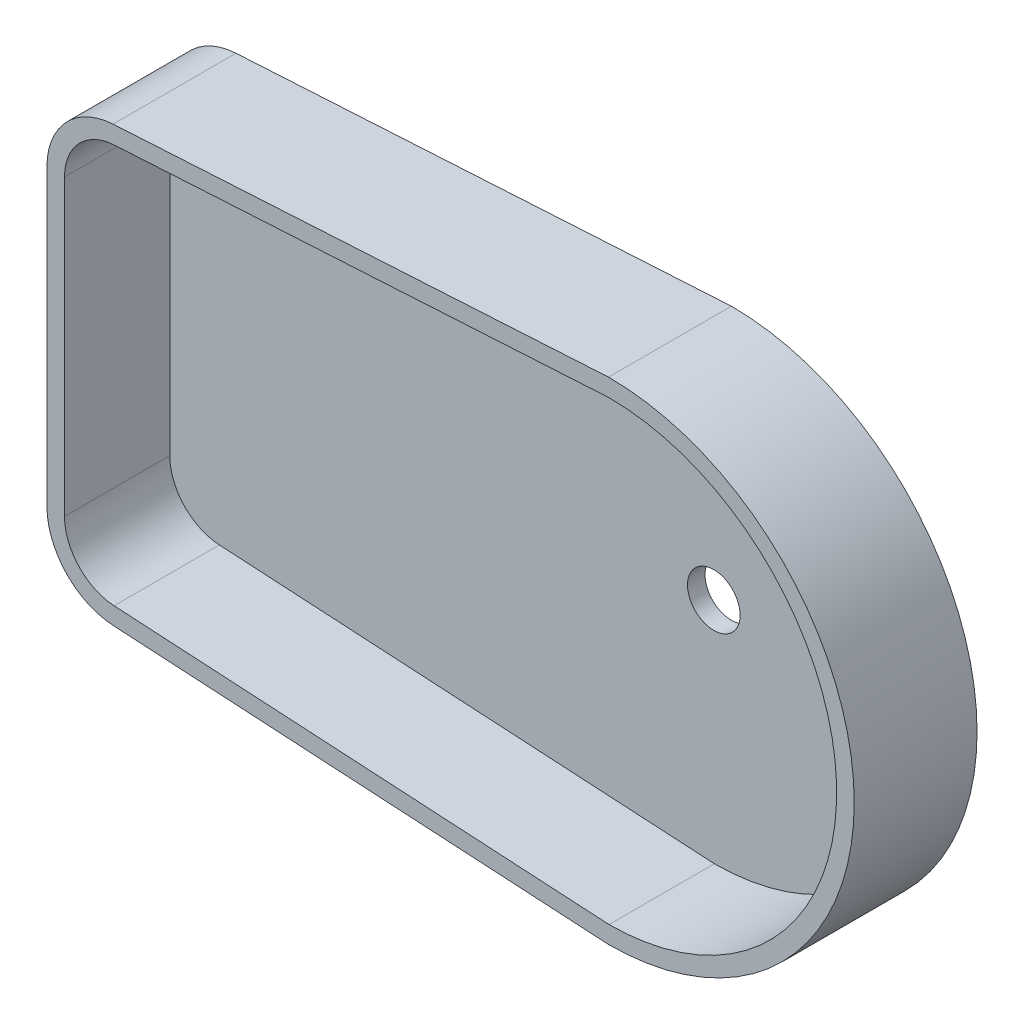
SolidWorks part; units mm, degrees
ref_plane "Front Plane" through (0, 0, 0) normal (0, 0, 1) x (1, 0, 0)
ref_plane "Top Plane" through (0, 0, 0) normal (0, 1, 0) x (1, 0, 0)
ref_plane "Right Plane" through (0, 0, 0) normal (1, 0, 0) x (0, 0, -1)
sketch "Sketch4" plane through (0, 0, 0) normal (0, 0, 1) x (1, 0, 0)
  line L0 (0, 0) -> (230, 0) construction
  line L1 (160, 107.8742) -> (160, -118.0659) construction
  line L2 (0, 41.8729) -> (0, -41.8729)
  line L3 (18.8457, 61.8395) -> (160, 70)
  line L4 (18.8457, -61.8395) -> (160, -70)
  arc A0 (160, -70) -> (160, 70) centre (160, 0) ccw
  arc A1 (18.8457, -61.8395) -> (0, -41.8729) centre (20, -41.8729) cw
  arc A2 (18.8457, 61.8395) -> (0, 41.8729) centre (20, 41.8729) ccw
  point P12 (0, -60.75)
  point P15 (0, 60.75)
  dimension "D3" = 140
  dimension "D5" = 20
  dimension "D1" = 230
  dimension "D2" = 70
  dimension "D4" = 121.5
extrude "Boss-Extrude1" add sketch "Sketch4" along normal mid plane 35
sketch "Sketch5" plane through (0, 0, 17.5) normal (0, 0, 1) x (1, 0, 0)
  line L7 (160.1417, 64.9998) -> (19.1343, 56.8479)
  line L8 (5, 41.8729) -> (5, -41.8729)
  line L9 (19.1343, -56.8479) -> (160.1417, -64.9998)
  line L10 (160.1417, 64.9998) -> (19.1343, 56.8479)
  line L11 (5, 41.8729) -> (5, -41.8729)
  line L12 (19.1343, -56.8479) -> (160.1417, -64.9998)
  arc A6 (160.1417, -64.9998) -> (160.1417, 64.9998) centre (160, 0) ccw
  arc A7 (19.1343, 56.8479) -> (5, 41.8729) centre (20, 41.8729) ccw
  arc A8 (5, -41.8729) -> (19.1343, -56.8479) centre (20, -41.8729) ccw
  arc A9 (160.1417, -64.9998) -> (160.1417, 64.9998) centre (160, 0) ccw
  arc A10 (19.1343, 56.8479) -> (5, 41.8729) centre (20, 41.8729) ccw
  arc A11 (5, -41.8729) -> (19.1343, -56.8479) centre (20, -41.8729) ccw
  dimension "D1" = 5
extrude "Cut-Extrude1" cut sketch "Sketch5" against normal blind 30
sketch "Sketch6" plane through (0, 0, -17.5) normal (0, 0, -1) x (-1, 0, 0)
  circle A1 centre (-160, 0) radius 7.5
  dimension "D4" = 15
extrude "Cut-Extrude2" cut sketch "Sketch6" against normal blind 10
